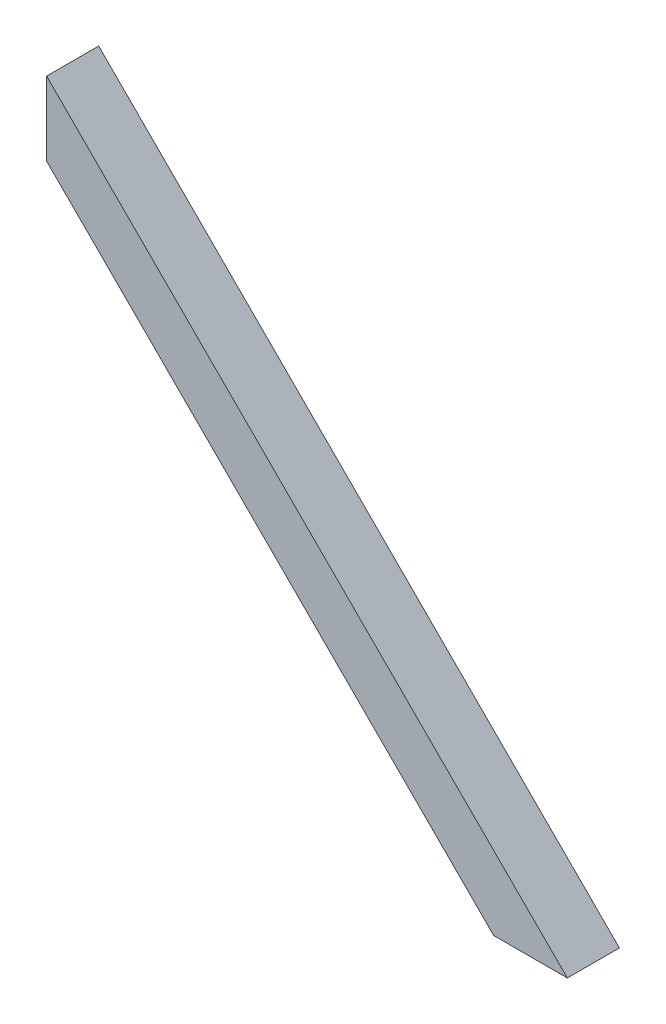
SolidWorks part; units mm, degrees
ref_plane "前视基准面" through (0, 0, 0) normal (0, 0, 1) x (1, 0, 0)
ref_plane "上视基准面" through (0, 0, 0) normal (0, 1, 0) x (1, 0, 0)
ref_plane "右视基准面" through (0, 0, 0) normal (1, 0, 0) x (0, 0, -1)
sketch "草图1" plane through (0, 0, 0) normal (0, 0, 1) x (1, 0, 0)
  line L0 (0, 300) -> (0, 0)
  line L1 (0, 0) -> (300, 0)
  line L2 (300, 0) -> (0, 300)
  line L3 (0, 257.5736) -> (257.5736, 0)
  dimension "D1" = 300
  dimension "D2" = 300
  dimension "D3" = 30
extrude "凸台-拉伸1" add sketch "草图1" along normal blind 30 contours L0 L3 L1 L2
